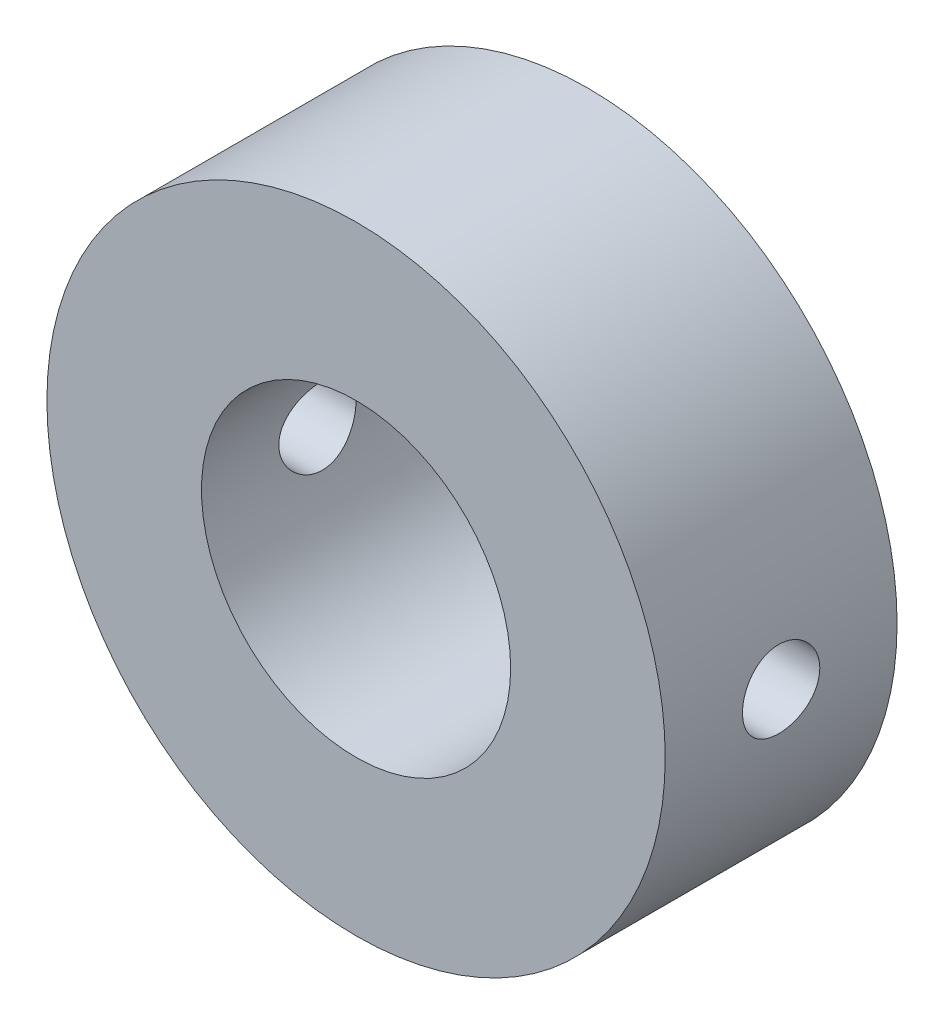
SolidWorks part; units mm, degrees
ref_plane "Front Plane" through (0, 0, 0) normal (0, 0, 1) x (1, 0, 0)
ref_plane "Top Plane" through (0, 0, 0) normal (0, 1, 0) x (1, 0, 0)
ref_plane "Right Plane" through (0, 0, 0) normal (1, 0, 0) x (0, 0, -1)
sketch "Sketch1" plane through (0, 0, 0) normal (0, 0, 1) x (1, 0, 0)
  circle A0 centre (0, 0) radius 8
  circle A1 centre (0, 0) radius 4
  dimension "D1" = 8
  dimension "D2" = 16
extrude "Boss-Extrude1" add sketch "Sketch1" along normal blind 6
hole_wizard "Ø2.0 (2) Diameter Hole1" positions "3DSketch1" profile "Sketch2" hole size "Ø2.0" standard "ISO" end condition through all
sketch3d "3DSketch1"
  point P0 (8, 0, 3)
  dimension "D1" = 3
  dimension "D2" = 0
sketch "Sketch2" plane through (8, 0, 3) normal (0, 1, 0) x (0, 0, -1)
  line L0 (0, 0) -> (0, 16)
  line L1 (0, 16) -> (1, 16)
  line L2 (1, 16) -> (1, 0)
  line L5 (1, 0) -> (0, 0)
  line L11 (0, -6.35) -> (0, 107.95) construction
  dimension "Thru Hole Dia." = 2
  dimension "Thru Hole Depth" = 16
